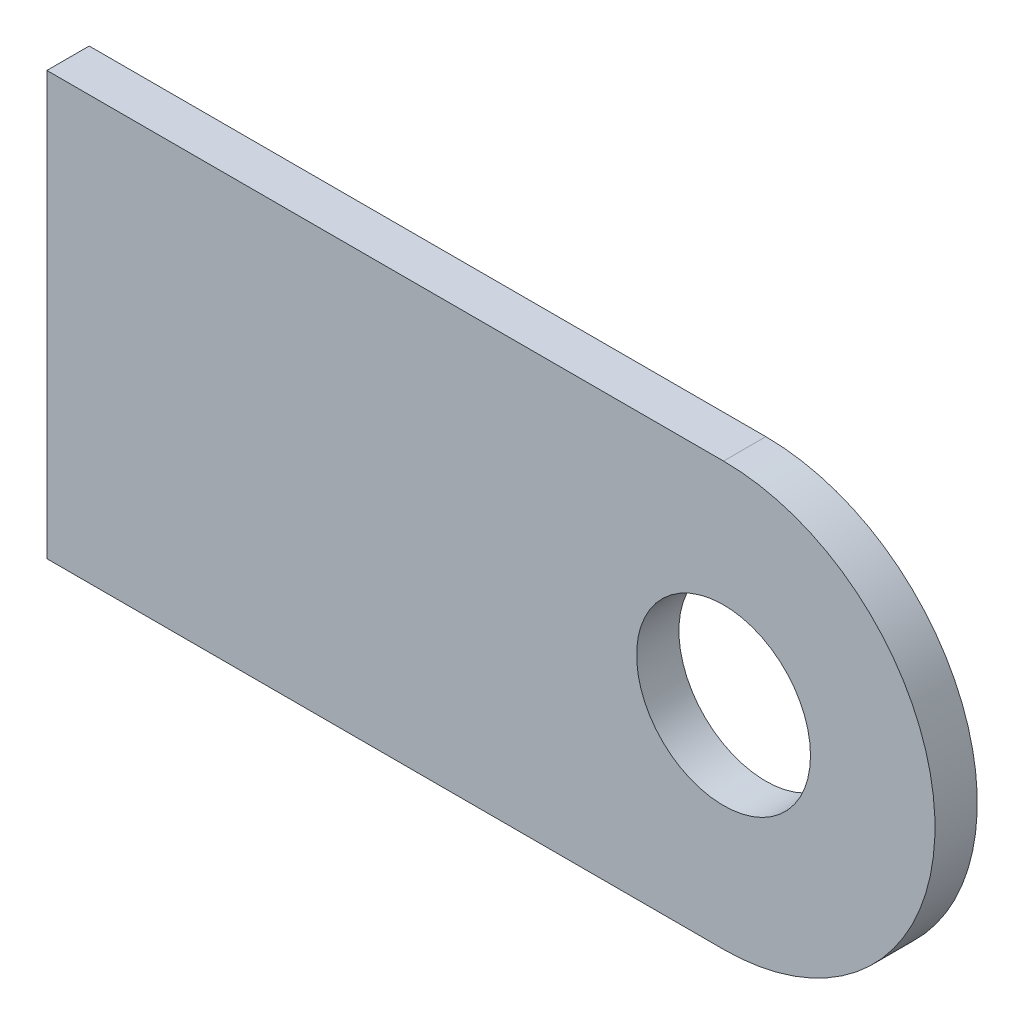
SolidWorks part; units mm, degrees
ref_plane "Front Plane" through (0, 0, 0) normal (0, 0, 1) x (1, 0, 0)
ref_plane "Top Plane" through (0, 0, 0) normal (0, 1, 0) x (1, 0, 0)
ref_plane "Right Plane" through (0, 0, 0) normal (1, 0, 0) x (0, 0, -1)
sketch "Sketch1" plane through (0, 0, 0) normal (0, 0, 1) x (1, 0, 0)
  line L0 (0, 15.875) -> (25.4, 15.875)
  line L1 (25.4, 0) -> (0, 0)
  line L2 (0, 0) -> (0, 15.875)
  circle A0 centre (25.4, 7.9375) radius 3.2639
  arc A1 (25.4, 15.875) -> (25.4, 0) centre (25.4, 7.9375) cw
  point P7 (0, 0)
  point P8 (0, 0)
  dimension "D2" = 6.5278
  dimension "D1" = 15.875
  dimension "D3" = 25.4
extrude "Boss-Extrude1" add sketch "Sketch1" along normal blind 1.5875
